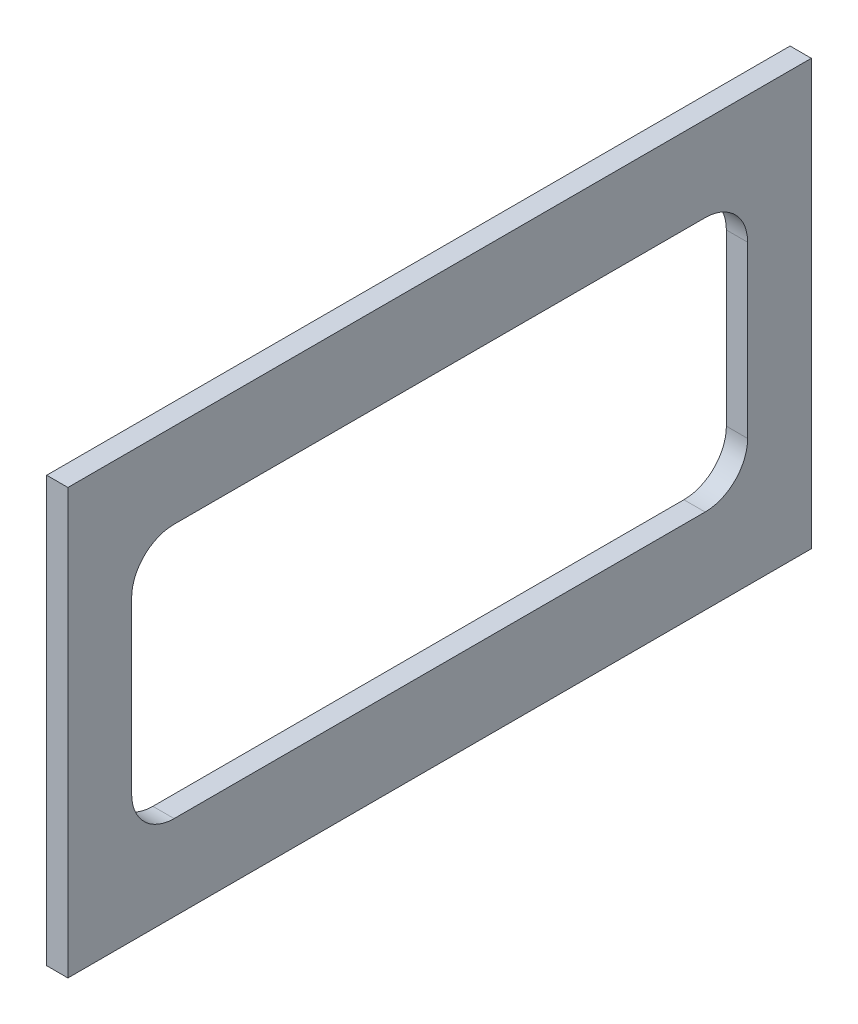
SolidWorks part; units mm, degrees
ref_plane "Front Plane" through (0, 0, 0) normal (0, 0, 1) x (1, 0, 0)
ref_plane "Top Plane" through (0, 0, 0) normal (0, 1, 0) x (1, 0, 0)
ref_plane "Right Plane" through (0, 0, 0) normal (1, 0, 0) x (0, 0, -1)
sketch "Sketch3" plane through (0, 0, 0) normal (1, 0, 0) x (0, 0, -1)
  line L1 (-55.5625, -31.75) -> (55.5625, -31.75)
  line L2 (-55.5625, -31.75) -> (-55.5625, 31.75)
  line L3 (-55.5625, 31.75) -> (55.5625, 31.75)
  line L4 (55.5625, -31.75) -> (55.5625, 31.75)
  line L5 (-55.5625, -31.75) -> (55.5625, 31.75) construction
  line L6 (-55.5625, 31.75) -> (55.5625, -31.75) construction
  line L7 (-39.6875, -19.05) -> (39.6875, -19.05)
  line L8 (-46.0375, -12.7) -> (-46.0375, 12.7)
  line L9 (-39.6875, 19.05) -> (39.6875, 19.05)
  line L10 (46.0375, -12.7) -> (46.0375, 12.7)
  line L11 (-46.0375, -19.05) -> (46.0375, 19.05) construction
  line L12 (-46.0375, 19.05) -> (46.0375, -19.05) construction
  arc A0 (-39.6875, -19.05) -> (-46.0375, -12.7) centre (-39.6875, -12.7) cw
  arc A1 (39.6875, -19.05) -> (46.0375, -12.7) centre (39.6875, -12.7) ccw
  arc A2 (39.6875, 19.05) -> (46.0375, 12.7) centre (39.6875, 12.7) cw
  arc A3 (-46.0375, 12.7) -> (-39.6875, 19.05) centre (-39.6875, 12.7) cw
  point P0 (0, 0)
  point P6 (0, 0)
  dimension "D5" = 6.35
  dimension "D1" = 63.5
  dimension "D2" = 111.125
  dimension "D3" = 9.525
  dimension "D4" = 12.7
extrude "Boss-Extrude1" add sketch "Sketch3" along normal blind 3.175
